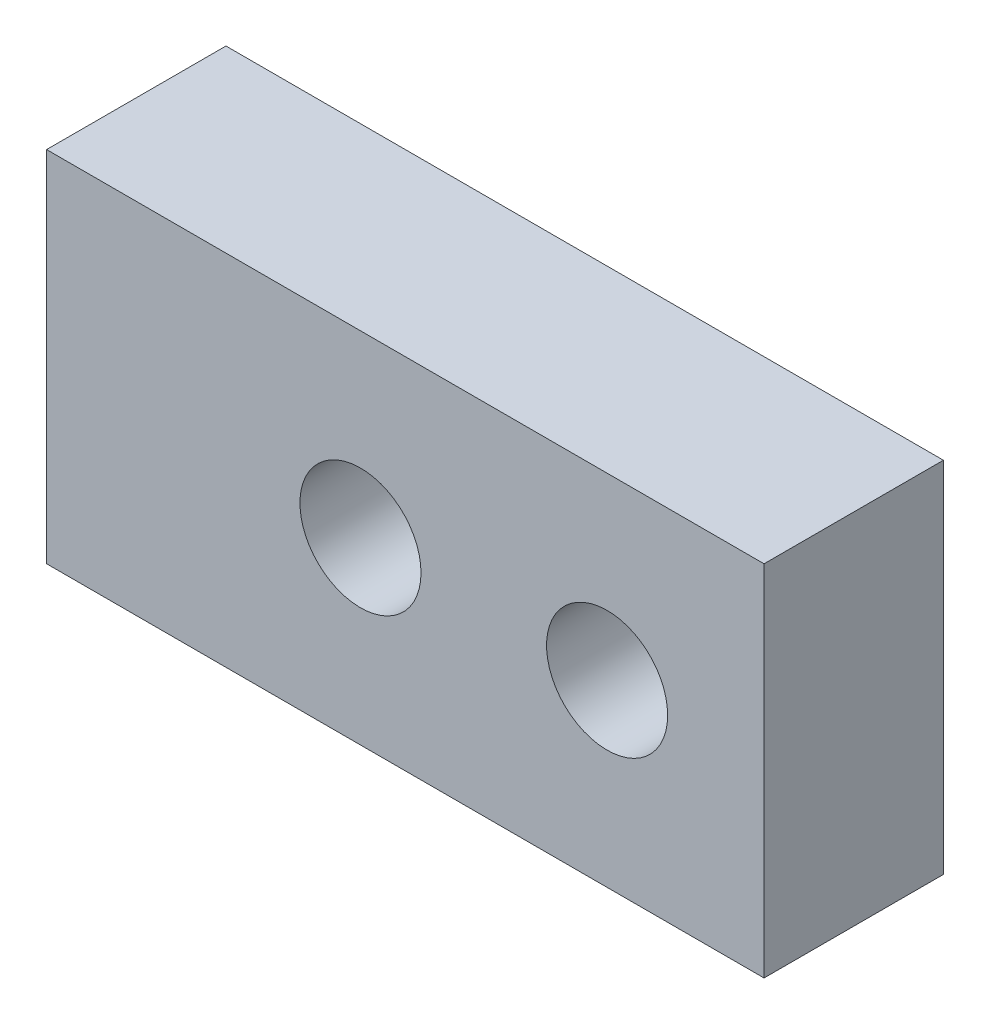
SolidWorks part; units mm, degrees
ref_plane "Front Plane" through (0, 0, 0) normal (0, 0, 1) x (1, 0, 0)
ref_plane "Top Plane" through (0, 0, 0) normal (0, 1, 0) x (1, 0, 0)
ref_plane "Right Plane" through (0, 0, 0) normal (1, 0, 0) x (0, 0, -1)
sketch "Sketch1" plane through (0, 0, 0) normal (0, 0, 1) x (1, 0, 0)
  line L1 (0, 0) -> (16, 0)
  line L2 (0, 0) -> (0, 8)
  line L3 (0, 8) -> (16, 8)
  line L4 (16, 0) -> (16, 8)
  circle A0 centre (12.5, 4) radius 1.35
  circle A1 centre (7, 4) radius 1.35
  point P9 (0, 0)
  point P10 (0, 0)
  point P12 (0, 0)
  dimension "D4" = 2.7
  dimension "D5" = 2.7
  dimension "D1" = 8
  dimension "D2" = 16
  dimension "D3" = 4
  dimension "D6" = 5.5
  dimension "D7" = 7
extrude "Boss-Extrude1" add sketch "Sketch1" along normal blind 4
